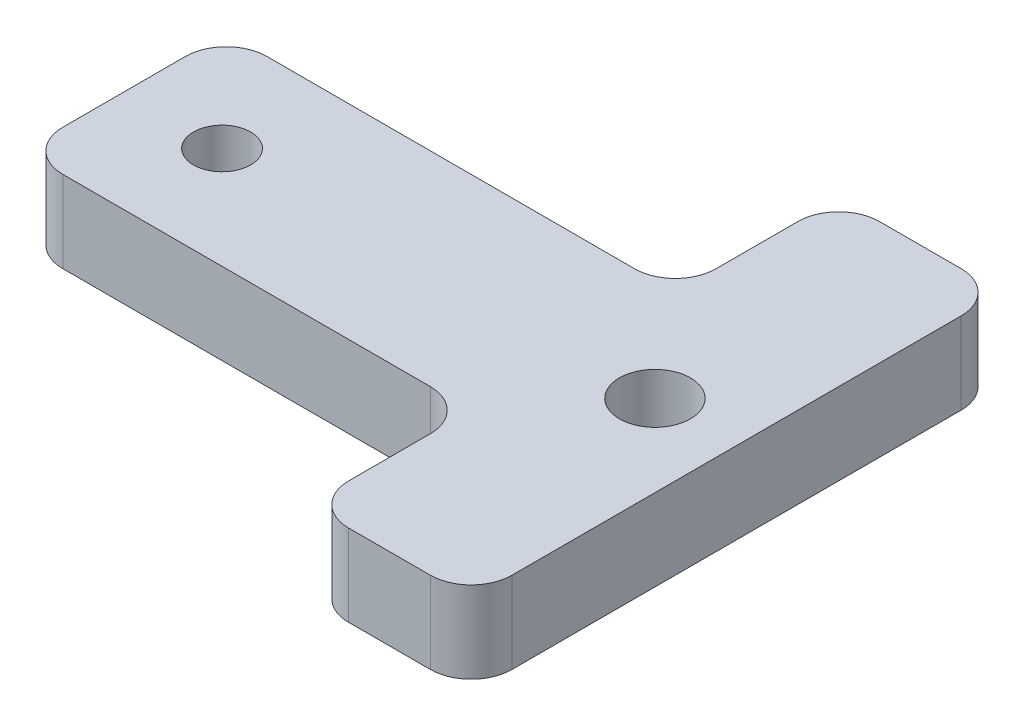
SolidWorks part; units mm, degrees
ref_plane "Front Plane" through (0, 0, 0) normal (0, 0, 1) x (1, 0, 0)
ref_plane "Top Plane" through (0, 0, 0) normal (0, 1, 0) x (1, 0, 0)
ref_plane "Right Plane" through (0, 0, 0) normal (1, 0, 0) x (0, 0, -1)
sketch "Sketch1" plane through (0, 0, 0) normal (0, 1, 0) x (1, 0, 0)
  line L0 (-55, 0) -> (55, 0) construction
  line L1 (-37.5, -12.5) -> (37.5, -12.5)
  line L2 (-37.5, -12.5) -> (-37.5, 12.5)
  line L3 (-37.5, 12.5) -> (37.5, 12.5)
  line L4 (37.5, -12.5) -> (37.5, 12.5)
  line L5 (-37.5, -12.5) -> (37.5, 12.5) construction
  line L6 (-37.5, 12.5) -> (37.5, -12.5) construction
  line L7 (37.5, 12.5) -> (17.5, 12.5)
  line L8 (37.5, 12.5) -> (37.5, 32.5)
  line L9 (37.5, 32.5) -> (17.5, 32.5)
  line L10 (17.5, 12.5) -> (17.5, 32.5)
  line L11 (37.5, -32.5) -> (17.5, -32.5)
  line L12 (17.5, -12.5) -> (17.5, -32.5)
  line L13 (37.5, -12.5) -> (17.5, -12.5)
  line L14 (37.5, -12.5) -> (37.5, -32.5)
  point P0 (0, 0)
  dimension "D1" = 25
  dimension "D2" = 75
  dimension "D3" = 20
  dimension "D4" = 20
extrude "Boss-Extrude1" add sketch "Sketch1" along normal blind 10 contours L10 L3 L8 L9 | L1 L4 L3 L2 | L14 L1 L12 L11
sketch "Sketch2" plane through (0, 10, 0) normal (0, 1, 0) x (1, 0, 0)
  line L0 (37.5, 32.5) -> (17.5, 32.5) construction
  line L1 (37.5, -32.5) -> (37.5, 32.5) construction
  line L2 (-37.5, -12.5) -> (-37.5, 12.5) construction
  circle A0 centre (-25.5, 0) radius 3.5
  circle A1 centre (27.5, 0) radius 4.35
  point P7 (27.5, 32.5)
  point P10 (37.5, 0)
  dimension "D2" = 7
  dimension "D3" = 8.7
  dimension "D1" = 12
extrude "Cut-Extrude1" cut sketch "Sketch2" against normal up to next
fillet "Fillet1" radius 5 8 edges at (37.5, 5, -32.5) (17.5, 5, -32.5) (17.5, 5, -12.5) (37.5, 5, 32.5) (17.5, 5, 32.5) (17.5, 5, 12.5) (-37.5, 5, -12.5) (-37.5, 5, 12.5)
sketch "Sketch3" plane through (0, 0, 0) normal (0, -1, 0) x (1, 0, 0)
  circle A0 centre (-25.5, 0) radius 6
  dimension "D1" = 12
extrude "Cut-Extrude2" cut sketch "Sketch3" against normal blind 4
